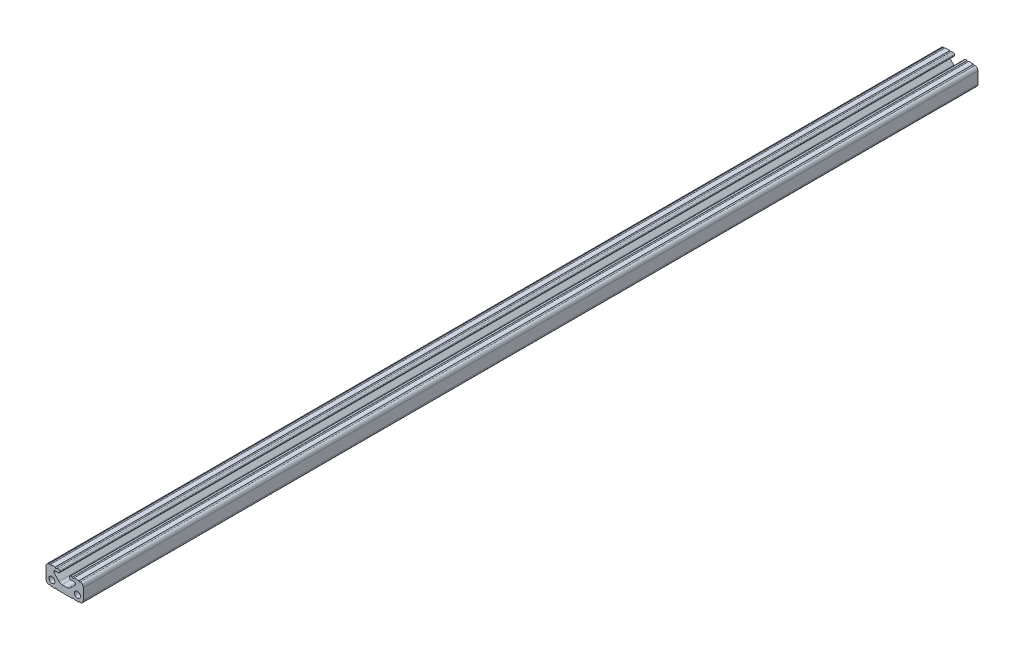
SolidWorks part; units mm, degrees
ref_plane "Front Plane" through (0, 0, 0) normal (0, 0, 1) x (1, 0, 0)
ref_plane "Top Plane" through (0, 0, 0) normal (0, 1, 0) x (1, 0, 0)
ref_plane "Right Plane" through (0, 0, 0) normal (1, 0, 0) x (0, 0, -1)
sketch "Sketch1" plane through (0, 0, 0) normal (0, 0, 1) x (1, 0, 0)
  line L0 (0, 6.35) -> (0, -6.35) construction
  line L1 (0, -6.35) -> (12.7, -6.35)
  line L2 (12.7, -6.35) -> (12.7, 6.35)
  line L3 (12.7, 6.35) -> (3.2512, 6.35)
  line L4 (3.2512, 6.35) -> (3.2512, 4.1402)
  line L5 (3.2512, 4.1402) -> (6.4224, 4.1402)
  line L6 (7.1255, 2.4426) -> (2.9811, -1.7018)
  line L7 (2.9811, -1.7018) -> (0, -1.7018)
  circle A0 centre (8.7249, -2.3876) radius 2.032
  arc A1 (6.4224, 4.1402) -> (7.1255, 2.4426) centre (6.4224, 3.1458) cw
  dimension "Center Hole Diameter" = 4.064
  dimension "D3" = 0.9944
  dimension "Rail Height" = 25.4
  dimension "Rail Width" = 12.7
  dimension "Hole CtoC" = 17.4498
  dimension "D1" = 3.9624
  dimension "T-Slot Width" = 6.5024
  dimension "Thickness" = 2.2098
  dimension "Inner Slot Width" = 14.8336
  dimension "Slot Depth" = 5.842
  dimension "D2" = 45
sketch "Sketch2" plane through (0, 0, 0) normal (1, 0, 0) x (0, 0, -1)
  line L0 (-304.8, -6.35) -> (304.8, -6.35) construction
  line L1 (-279.4, 0) -> (279.4, 0) construction
  dimension "Length" = 609.6
  dimension "D1" = 25.4
sketch "Sketch3" plane through (0, 0, 0) normal (0, 0, 1) x (1, 0, 0)
  line L0 (3.2512, 6.35) -> (3.2512, 4.1402) construction
  line L1 (12.7, 6.35) -> (3.2512, 6.35) construction
  line L2 (3.2512, 4.1402) -> (6.4224, 4.1402) construction
  line L3 (3.2512, 5.3556) -> (3.2512, 5.1346)
  line L4 (12.7, -6.35) -> (12.7, 6.35) construction
  line L5 (0, -6.35) -> (12.7, -6.35) construction
  line L6 (2.9811, -1.7018) -> (0, -1.7018) construction
  line L7 (7.1255, 2.4426) -> (2.9811, -1.7018) construction
  line L8 (0, -1.7018) -> (1.7454, -1.7018)
  line L9 (4.2456, 4.1402) -> (6.4224, 4.1402)
  line L10 (3.8549, -0.828) -> (7.1255, 2.4426)
  line L11 (0, -1.7018) -> (0, -6.35)
  line L12 (0, -6.35) -> (10.16, -6.35)
  line L13 (12.7, -3.81) -> (12.7, 3.81)
  line L14 (4.2456, 6.35) -> (10.16, 6.35)
  arc A0 (3.2512, 5.3556) -> (4.2456, 6.35) centre (4.2456, 5.3556) cw
  arc A1 (3.2512, 5.1346) -> (4.2456, 4.1402) centre (4.2456, 5.1346) ccw
  arc A2 (7.1255, 2.4426) -> (6.4224, 4.1402) centre (6.4224, 3.1458) ccw construction
  arc A3 (10.16, 6.35) -> (12.7, 3.81) centre (10.16, 3.81) cw
  arc A4 (10.16, -6.35) -> (12.7, -3.81) centre (10.16, -3.81) ccw
  arc A5 (7.1255, 2.4426) -> (6.4224, 4.1402) centre (6.4224, 3.1458) ccw
  circle A6 centre (8.7249, -2.3876) radius 2.032 construction
  circle A7 centre (8.7249, -2.3876) radius 2.032
  arc A8 (1.7454, -1.7018) -> (3.8549, -0.828) centre (1.7454, 1.2814) ccw
  dimension "D2" = 2.9832
  dimension "D1" = 2.54
extrude "Boss-Extrude1" add sketch "Sketch3" along normal mid plane 609.6
sketch "Sketch4" plane through (0, 0, 0) normal (0, 0, 1) x (1, 0, 0)
  line L0 (12.7, 6.35) -> (3.2512, 6.35) construction
  line L1 (0, -6.35) -> (12.7, -6.35) construction
  line L2 (10.7569, -2.3876) -> (10.7569, 6.35) construction
  line L3 (6.4224, 3.1458) -> (6.4224, 6.35) construction
  circle A0 centre (5.8699, 6.35) radius 0.5524
  circle A1 centre (10.2045, 6.35) radius 0.5524
  circle A2 centre (5.8699, -6.35) radius 0.5524
  circle A3 centre (10.2045, -6.35) radius 0.5524
  circle A4 centre (8.7249, -2.3876) radius 2.032 construction
  dimension "D1" = 1.1049
extrude "Cut-Extrude1" cut sketch "Sketch4" against normal through all both and the other way through all
mirror "Mirror1" about plane through (0, 0, 0) normal (1, 0, 0) of bodies 135
equation "\"D3@Sketch1\"=\"Thickness@Sketch1\"*0.45"
equation "\"D1@Sketch3\"=\"Rail Width@Sketch1\"*0.2"
equation "\"D2@Sketch3\"=\"D3@Sketch1\"*3"
equation "\"D1@Boss-Extrude1\"=\"length@sketch2\""
equation "\"D1@Sketch4\"=\"Thickness@Sketch1\"*0.5"
